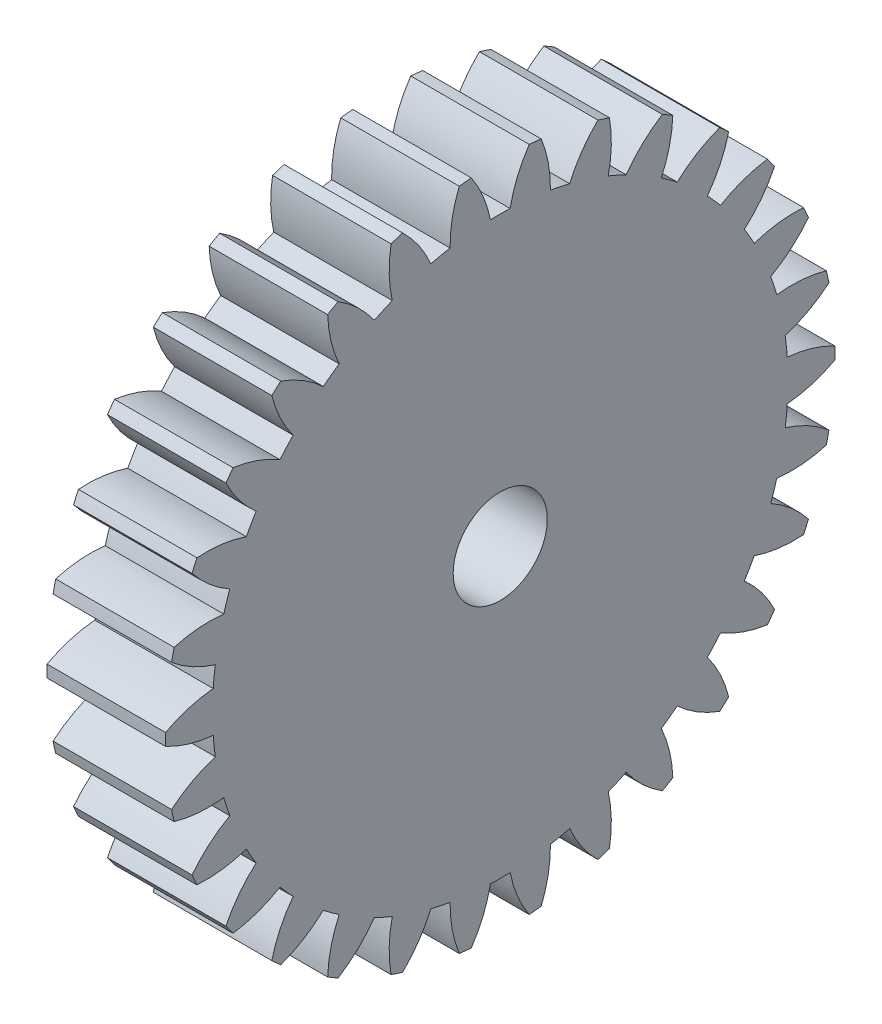
SolidWorks part; units mm, degrees
material "ABS"
ref_plane "Plane1" through (0, 0, 0) normal (0, 0, 1) x (1, 0, 0)
ref_plane "Plane2" through (0, 0, 0) normal (0, 1, 0) x (1, 0, 0)
ref_plane "Plane3" through (0, 0, 0) normal (1, 0, 0) x (0, 0, -1)
other "Configuration Table"
sketch "HoldingSke" plane through (0, 0, 0) normal (0, 1, 0) x (1, 0, 0)
  line L0 (0, 0) -> (527.9291, -304.8)
  line L1 (-15, 0) -> (100, 0) construction
  line L2 (0, 0) -> (-2.1039, 2.3779)
  line L3 (0, 0) -> (-11.863, 4.5341)
  line L4 (0, 0) -> (7.479, 4.318)
  line L5 (0, 0) -> (-47.5972, -17.7524)
  line L6 (0, 0) -> (-4.9691, -3.3527)
  line L7 (-2.1039, 2.3779) -> (8.8308, 51.9871)
  line L8 (-76.2, 54.61) -> (-71.1708, 54.61)
  line L9 (-71.009, 38.7566) -> (-53.1078, 45.2721)
  line L10 (-76.2, 71.12) -> (104.1128, 71.12)
  line L11 (0, 0) -> (-5.9944, 0)
  line L12 (-76.2, 101.6) -> (-76.1573, 101.6)
  line L13 (24.9733, 27.94) -> (52.9518, 28.4284)
  line L14 (24.9733, 27.94) -> (25.0241, 27.9398)
  line L15 (24.9733, 27.94) -> (100.4021, 29.52)
  circle A0 centre (0, 0) radius 2.3813
  circle A1 centre (0, 0) radius 14.5542
  circle A2 centre (0, 0) radius 38.1
  circle A3 centre (0, 0) radius 2.3813
  dimension "MHD" = 29.1084
  dimension "Hub_dia" = 76.2
  dimension "Bore" = 4.7625
  dimension "MBD" = 4.7625
  dimension "Num_teeth" = 30
  dimension "Pitch" = 609.6
  dimension "Overall_len" = 50.8
  dimension "Show_teeth" = 30
  dimension "Thickness" = 5.9944
  dimension "OAL" = 50.8001
  dimension "T_dim" = 5.0292
  dimension "Ap" = 20
  dimension "H" = 19.05
  dimension "Pitch_radius" = 180.3128
  dimension "Width" = 5.9944
  dimension "Backlash" = 0.0427
  dimension "Addendum_fac" = 1
  dimension "Dedendum_fac" = 1.2
  dimension "Clearance_fac" = 0.2
  dimension "Dedendum_add" = 0.0508
sketch "BasProSke" plane through (0, 0, 0) normal (0, 1, 0) x (1, 0, 0)
  line L0 (-10, 0) -> (60, 0) construction
  line L1 (0, 0) -> (0, 16.9333)
  line L2 (0, 0) -> (5.9944, 0)
  line L3 (5.9944, 0) -> (5.9944, 16.9333)
  line L4 (5.9944, 16.9333) -> (0, 16.9333)
  dimension "Thickness" = 5.9944
  dimension "Diameter" = 33.8667
revolve "Base-Revolve" add sketch "BasProSke" angle 360 about L0
sketch "TooCutSke" plane through (0, 0, 0) normal (1, 0, 0) x (0, 0, -1)
  line L1 (0, 0) -> (0, 107) construction
  line L2 (0, 0) -> (-0.9055, 15.8492) construction
  line L3 (0, 0) -> (-3.315, 31.5402) construction
  line L4 (-0.9055, 15.8492) -> (-1.6575, 15.7701) construction
  arc A0 (0.4982, 14.5457) -> (-0.4982, 14.5457) centre (0, 0) ccw
  arc A1 (1.4826, 16.8938) -> (-1.4826, 16.8938) centre (0, 0) ccw
  circle A2 centre (0, 0) radius 15.875 construction
  circle A3 centre (0, 0) radius 14.9176 construction
  arc A4 (-0.4982, 14.5457) -> (-1.4826, 16.8938) centre (-6.7277, 13.3144) ccw
  arc A5 (1.4826, 16.8938) -> (0.4982, 14.5457) centre (6.7277, 13.3144) ccw
  dimension "Root_dia" = 29.1084
  dimension "Overcut_dia" = 33.9175
  dimension "Pitch_dia" = 31.75
  dimension "Base_dia" = 29.8352
  dimension "Flank_rad" = 6.35
  dimension "Half_ang" = 6
  dimension "Half_CT" = 0.7562
extrude "ToothCut" cut sketch "TooCutSke" along normal through all
fillet "Breaks" [suppressed] radius 0.0212
fillet "RootFillets" [suppressed] radius 0.2625
pattern_circular "TeethCuts" count 30 every 12 about axis through (-10, 0, 0) along (1, 0, 0) of "ToothCut", "RootFillets", "Breaks"
sketch "HubNeaOneSke" plane through (0, 0, 0) normal (-1, 0, 0) x (0, 0, 1)
  circle A0 centre (0, 0) radius 14.5542
  dimension "Diameter" = 29.1084
extrude "HubNearOne" [suppressed] add sketch "HubNeaOneSke" along normal blind 44.8057
sketch "HubNeaBotSke" plane through (0, 0, 0) normal (-1, 0, 0) x (0, 0, 1)
  circle A0 centre (0, 0) radius 14.5542
  dimension "Diameter" = 29.1084
extrude "HubNearBoth" [suppressed] add sketch "HubNeaBotSke" along normal blind 22.4028
ref_plane "FarPln" through (5.9944, 0, 0) normal (1, 0, 0) x (0, 0, -1)
sketch "HubFarSke" plane through (5.9944, 0, 0) normal (1, 0, 0) x (0, 0, -1)
  circle A0 centre (0, 0) radius 14.5542
  dimension "Diameter" = 29.1084
extrude "HubFar" [suppressed] add sketch "HubFarSke" along normal blind 22.4028
sketch "BorSke" plane through (0, 0, 0) normal (1, 0, 0) x (0, 0, -1)
  circle A0 centre (0, 0) radius 2.3813
  dimension "Diameter" = 4.7625
extrude "Bore" cut sketch "BorSke" along normal mid plane 101.6001
sketch "KeySke" plane through (0, 0, 0) normal (1, 0, 0) x (0, 0, -1)
  line L0 (-0.127, 0) -> (-0.127, 2.648)
  line L1 (-0.127, 2.648) -> (0.127, 2.648)
  line L2 (0.127, 2.648) -> (0.127, 0)
  line L3 (0, 0) -> (0, 34) construction
  line L4 (-0.127, 0) -> (0.127, 0)
  dimension "Offset" = 2.648
  dimension "Width" = 0.254
extrude "Keyway" [suppressed] cut sketch "KeySke" along normal mid plane 101.6001
pattern_circular "Keyway2" [suppressed] count 2 every 90 about axis through (-10, 0, 0) along (1, 0, 0)
equation "' \"Pitch@HoldingSke\" = 4"
equation "' \"Num_teeth@HoldingSke\" = 12"
equation "' \"Ap@HoldingSke\" =  20"
equation "' \"Ap@HoldingSke\" = 20"
equation "' \"Width@HoldingSke\" = 0.5"
equation "' \"Hub_dia@HoldingSke\"= 1"
equation "' \"Hub_dia@HoldingSke\" = 1"
equation "' \"Overall_len@HoldingSke\" = 1.0"
equation "' \"Bore@HoldingSke\" = 0.75"
equation "' \"T_dim@HoldingSke\" = 0.85"
equation "' \"Width@KeySke\" = 0.25"
equation "' \"Show_teeth@HoldingSke\" = 13"
equation "' \"Backlash@HoldingSke\" = 0.009"
equation "' \"Addendum_fac@HoldingSke\" = 1.0"
equation "' \"Dedendum_fac@HoldingSke\" = 1.25"
equation "' \"Dedendum_add@HoldingSke\" = 0.00005"
equation "' \"Clearance_fac@HoldingSke\" = 0.25"
equation "' \"Pitch@HoldingSke\" = 0.5"
equation "' \"Num_teeth@HoldingSke\" = 23"
equation "' \"Show_teeth@HoldingSke\" = 23"
equation "' \"Backlash@HoldingSke\" = 0.0375"
equation "\"Overcut_dia@TooCutSke\" = (\"Num_teeth@HoldingSke\" + 2 * \"Addendum_fac@HoldingSke\") / \"Pitch@HoldingSke\" + 0.002"
equation "\"Pitch_dia@TooCutSke\" = \"Num_teeth@HoldingSke\" / \"Pitch@HoldingSke\""
equation "\"Base_dia@TooCutSke\" = \"Num_teeth@HoldingSke\" / \"Pitch@HoldingSke\" * cos((\"Ap@HoldingSke\"  * 3.14159265 / 180))"
equation "\"Root_dia@TooCutSke\" = (\"Num_teeth@HoldingSke\" + 2) / \"Pitch@HoldingSke\" - 2 * (\"Addendum_fac@HoldingSke\" + \"Dedendum_fac@HoldingSke\") / \"Pitch@HoldingSke\" - \"Dedendum_add@HoldingSke\" * 2"
equation "\"Half_ang@TooCutSke\" = 180 / \"Num_teeth@HoldingSke\""
equation "\"Half_CT@TooCutSke\" = \"Num_teeth@HoldingSke\" / \"Pitch@HoldingSke\" * sin((3.14159265 / 2 / \"Num_teeth@HoldingSke\")) / 2 - 7 * \"Backlash@HoldingSke\" / 4"
equation "\"Flank_rad@TooCutSke\" = \"Num_teeth@HoldingSke\" / \"Pitch@HoldingSke\" / 5"
equation "\"Radius@RootFillets\" = \"Clearance_fac@HoldingSke\" / \"Pitch@HoldingSke\" + \"Dedendum_add@HoldingSke\""
equation "\"Break_rad@Breaks\" = 0.02 / \"Pitch@HoldingSke\""
equation "\"Thickness@HoldingSke\" = \"Width@HoldingSke\""
equation "\"OAL@HoldingSke\" = \"Thickness@HoldingSke\""
equation "\"MHD@HoldingSke\" = (\"Num_teeth@HoldingSke\" + 2) / \"Pitch@HoldingSke\" - 2 * (\"Addendum_fac@HoldingSke\" + \"Dedendum_fac@HoldingSke\")  / \"Pitch@HoldingSke\" - \"Dedendum_add@HoldingSke\" * 2"
equation "\"MBD@HoldingSke\" = (\"Num_teeth@HoldingSke\" + 2) / \"Pitch@HoldingSke\" - 2 * (\"Addendum_fac@HoldingSke\" + \"Dedendum_fac@HoldingSke\")  / \"Pitch@HoldingSke\" - \"Dedendum_add@HoldingSke\" * 2 - 0.002"
equation "\"MHD@HoldingSke\" = ((sgn( \"MHD@HoldingSke\" - \"Hub_dia@HoldingSke\" )-1)*( \"MHD@HoldingSke\" - \"Hub_dia@HoldingSke\" ))/-2+ \"Hub_dia@HoldingSke\""
equation "\"MBD@HoldingSke\" = ((sgn( \"MBD@HoldingSke\" - \"Bore@HoldingSke\" )-1)*( \"MBD@HoldingSke\" - \"Bore@HoldingSke\" ))/-2+ \"Bore@HoldingSke\""
equation "\"OAL@HoldingSke\" = ((sgn( \"OAL@HoldingSke\" - \"Overall_len@HoldingSke\" )+1)*( \"OAL@HoldingSke\" - \"Overall_len@HoldingSke\" ))/2 + \"Overall_len@HoldingSke\" + 0.000002"
equation "\"Num_teeth@TeethCuts\" = int( \"Show_teeth@HoldingSke\" ) + 1"
equation "\"Num_teeth@TeethCuts\" = ((sgn( \"Num_teeth@TeethCuts\" - \"Num_teeth@HoldingSke\" )-1)*( \"Num_teeth@TeethCuts\" - \"Num_teeth@HoldingSke\" ))/-2+ \"Num_teeth@HoldingSke\""
equation "\"Num_teeth@TeethCuts\" = ((sgn( \"Num_teeth@TeethCuts\" - 2.0)+1)*( \"Num_teeth@TeethCuts\" - 2.0))/2 +2.0"
equation "\"Angle@TeethCuts\" = 360.0 / \"Num_teeth@HoldingSke\""
equation "\"Diameter@BasProSke\" = (\"Num_teeth@HoldingSke\" + 2 * \"Addendum_fac@HoldingSke\") / \"Pitch@HoldingSke\""
equation "\"Thickness@BasProSke\"  = \"Thickness@HoldingSke\""
equation "' \"Fillet_rad@BasProSke\" =  \"Thickness@HoldingSke\" * 0.05"
equation "' \"Fillet_rad@BasProSke\" = \"Thickness@HoldingSke\" * 0.05"
equation "\"MHD@HoldingSke\" = ((sgn( \"MHD@HoldingSke\" - \"Root_dia@TooCutSke\" )-1)*( \"MHD@HoldingSke\" - \"Root_dia@TooCutSke\" ))/-2+ \"Root_dia@TooCutSke\""
equation "\"Diameter@HubNeaOneSke\" = \"MHD@HoldingSke\""
equation "\"Length@HubNearOne\" = \"OAL@HoldingSke\" - \"Thickness@BasProSke\""
equation "\"Diameter@HubNeaBotSke\" = \"MHD@HoldingSke\""
equation "\"Length@HubNearBoth\" = ( \"OAL@HoldingSke\" - \"Thickness@BasProSke\" ) / 2.0"
equation "\"Thickness@FarPln\" = \"Thickness@BasProSke\""
equation "\"Diameter@HubFarSke\" = \"MHD@HoldingSke\""
equation "\"Length@HubFar\" = ( \"OAL@HoldingSke\" - \"Thickness@BasProSke\" ) / 2.0"
equation "\"Diameter@BorSke\" = \"MBD@HoldingSke\""
equation "\"D1@Bore\" = \"OAL@HoldingSke\" * 2.0"
equation "\"D1@Keyway\" = \"OAL@HoldingSke\" * 2.0"
equation "\"Offset@KeySke\" = \"T_dim@HoldingSke\" - \"MBD@HoldingSke\" / 2.0"
